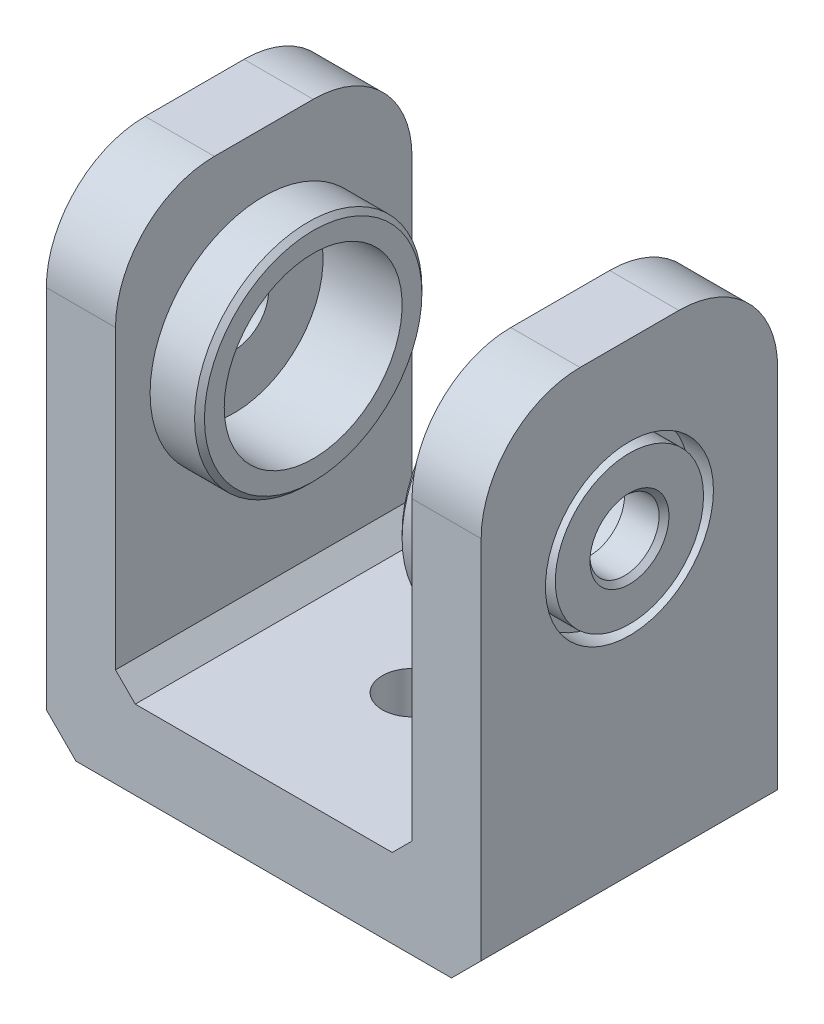
SolidWorks part; units mm, degrees
ref_plane "前视基准面" through (0, 0, 0) normal (0, 0, 1) x (1, 0, 0)
ref_plane "上视基准面" through (0, 0, 0) normal (0, 1, 0) x (1, 0, 0)
ref_plane "右视基准面" through (0, 0, 0) normal (1, 0, 0) x (0, 0, -1)
other "Configuration Table"
sketch "草图1" plane through (0, 0, 0) normal (0, 1, 0) x (1, 0, 0)
  circle A1 centre (0, 0) radius 10
  dimension "D2" = 20
extrude "凸台-拉伸1" add sketch "草图1" along normal blind 13
sketch "草图4" plane through (0, 13, 0) normal (0, 1, 0) x (1, 0, 0)
  line L1 (3, 0) -> (-1.5, 2.5981)
  line L2 (3, 0) -> (-1.5, 2.5981)
  arc A1 (-1.5, 2.5981) -> (3, 0) centre (0, 0) ccw
  arc A2 (-1.5, 2.5981) -> (3, 0) centre (0, 0) ccw
  dimension "D1" = 0
extrude "切除-拉伸2" cut sketch "草图4" against normal through all
sketch "草图7" plane through (0, 0, 0) normal (0, -1, 0) x (1, 0, 0)
  line L1 (-15, 15) -> (15, 15)
  line L2 (-15, 15) -> (-15, -15)
  line L3 (-15, -15) -> (15, -15)
  line L4 (15, 15) -> (15, -15)
  line L5 (-15, 15) -> (15, -15) construction
  line L6 (-15, -15) -> (15, 15) construction
  circle A0 centre (0, 0) radius 10
  dimension "D1" = 20
  dimension "D2" = 30
  dimension "D3" = 30
extrude "凸台-拉伸2" add sketch "草图7" against normal blind 8
sketch "草图11" plane through (0, 0, 0) normal (0, -1, 0) x (1, 0, 0)
  line L0 (-15, -15) -> (15, -15) construction
  line L1 (-15, 15) -> (-22, 15)
  line L2 (-15, 15) -> (-15, -15)
  line L3 (-15, -15) -> (-22, -15)
  line L4 (-22, 15) -> (-22, -15)
  line L5 (15, 15) -> (22, 15)
  line L6 (15, 15) -> (15, -15)
  line L7 (15, -15) -> (22, -15)
  line L8 (22, 15) -> (22, -15)
  dimension "D1" = 7
  dimension "D2" = 7
extrude "凸台-拉伸6" add sketch "草图11" against normal blind 50
fillet "圆角2" radius 10 4 edges at (18.5, 50, 15) (18.5, 50, -15) (-18.5, 50, -15) (-18.5, 50, 15)
sketch "草图12" plane through (22, 0, 0) normal (1, 0, 0) x (0, 0, -1)
  arc A0 (8.4173, 31.317) -> (8.4173, 33.683) centre (0, 32.5) ccw construction
  arc A1 (7.427, 31.4562) -> (7.427, 33.5438) centre (0, 32.5) ccw construction
  arc A2 (8.4173, 31.317) -> (8.4173, 33.683) centre (0, 32.5) ccw
  arc A3 (7.427, 31.4562) -> (7.427, 33.5438) centre (0, 32.5) ccw
sketch "草图13" plane through (22, 0, 0) normal (1, 0, 0) x (0, 0, -1)
  circle A0 centre (0, 32.5) radius 7.5
  circle A1 centre (0, 32.5) radius 8.5
  dimension "D1" = 15
  dimension "D2" = 17
extrude "切除-拉伸3" cut sketch "草图13" against normal blind 2.5
sketch "草图14" plane through (22, 0, 0) normal (1, 0, 0) x (0, 0, -1)
  circle A0 centre (0, 32.5) radius 3.5
  dimension "D1" = 7
extrude "切除-拉伸4" cut sketch "草图14" against normal up to surface (37 mm away)
sketch "草图22" plane through (0, 0, 0) normal (0, -1, 0) x (1, 0, 0)
  line L0 (-22, -15) -> (22, -15) construction
  line L1 (10, -15) -> (-10, -15)
  line L2 (10, -15) -> (10, -21)
  line L3 (10, -21) -> (-10, -21)
  line L4 (-10, -15) -> (-10, -21)
  line L6 (22, -15) -> (22, 15) construction
  line L7 (-22, 15) -> (-22, -15) construction
  dimension "D1" = 6
  dimension "D2" = 12
  dimension "D3" = 12
extrude "凸台-拉伸8" add sketch "草图22" against normal blind 18.5
chamfer "倒角7" distance 2 angle 45 2 edges at (-10, 4, -15) (10, 4, -15)
sketch "草图23" plane through (15, 0, 0) normal (-1, 0, 0) x (0, 0, 1)
  circle A0 centre (0, 32.5) radius 9
  dimension "D1" = 18
extrude "切除-拉伸6" cut sketch "草图23" against normal blind 3
chamfer "倒角8" distance 2 angle 45 4 edges at (10, 9.25, -21) (10, 18.5, -18) (-10, 9.25, -21) (-10, 18.5, -18)
sketch "草图24" plane through (0, 13, 0) normal (0, 1, 0) x (1, 0, 0)
  circle A0 centre (0, 0) radius 10
  dimension "D1" = 20
extrude "切除-拉伸7" cut sketch "草图24" against normal up to surface (5 mm away) up to face at (0, 8, -10)
sketch "草图25" plane through (0, 0, 0) normal (0, -1, 0) x (1, 0, 0)
  circle A0 centre (0, 0) radius 3
  dimension "D1" = 6
extrude "切除-拉伸8" cut sketch "草图25" against normal blind 2
chamfer "倒角9" distance 3 angle 45 2 edges at (22, 0, 0) (-22, 0, 0)
chamfer "倒角10" distance 1 angle 45 1 edges at (0, 0, 3)
chamfer "倒角3" distance 2 angle 45 3 edges at (15, 8, 0) (-15, 8, 0) (0, 8, -15)
sketch "草图26" plane through (15, 0, 0) normal (-1, 0, 0) x (0, 0, 1)
  circle A0 centre (0, 32.5) radius 9
  circle A1 centre (0, 32.5) radius 11.5
  circle A2 centre (0, 32.5) radius 9 construction
  dimension "D1" = 23
extrude "凸台-拉伸9" add sketch "草图26" along normal blind 5
mirror "镜向2" about plane through (0, 0, 0) normal (1, 0, 0) of "凸台-拉伸9", "切除-拉伸3", "切除-拉伸4", "切除-拉伸6"
chamfer "倒角4" distance 0.5 angle 45 4 edges at (22, 32.5, -3.5) (-22, 32.5, -3.5) (-10, 32.5, 11.5) (10, 32.5, 11.5)
